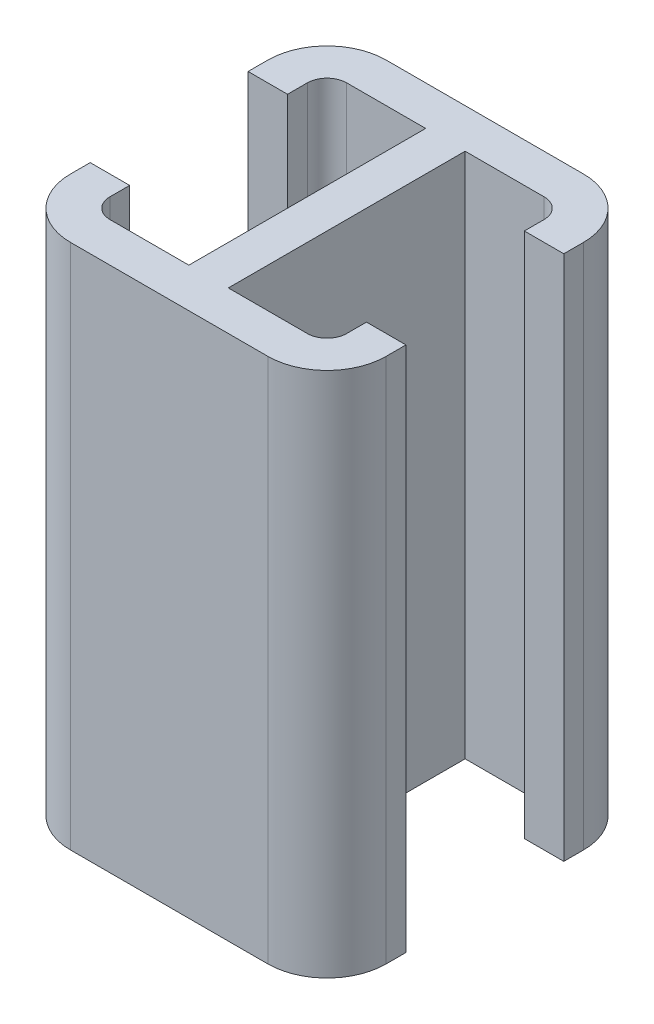
SolidWorks part; units mm, degrees
ref_plane "正面" through (0, 0, 0) normal (0, 0, 1) x (1, 0, 0)
ref_plane "平面" through (0, 0, 0) normal (0, 1, 0) x (1, 0, 0)
ref_plane "右側面" through (0, 0, 0) normal (1, 0, 0) x (0, 0, -1)
sketch "ｽｹｯﾁ5" plane through (0, 0, 0) normal (0, 1, 0) x (1, 0, 0)
  line L1 (0, 0) -> (120, 0)
  line L2 (0, 0) -> (0, 30)
  line L3 (0, 120) -> (120, 120)
  line L4 (120, 0) -> (120, 30)
  line L6 (52.5, 105) -> (15, 105)
  line L7 (52.5, 105) -> (52.5, 15)
  line L8 (52.5, 15) -> (15, 15)
  line L9 (15, 105) -> (15, 90)
  line L11 (15, 90) -> (0, 90)
  line L13 (15, 30) -> (0, 30)
  line L16 (67.5, 105) -> (105, 105)
  line L17 (67.5, 105) -> (67.5, 15)
  line L18 (67.5, 15) -> (105, 15)
  line L19 (105, 105) -> (105, 90)
  line L20 (0, 90) -> (0, 120)
  line L21 (105, 90) -> (120, 90)
  line L23 (105, 30) -> (120, 30)
  line L25 (15, 30) -> (15, 15)
  line L26 (120, 90) -> (120, 120)
  line L27 (105, 30) -> (105, 15)
  point P0 (0, 0)
  point P1 (0, 30)
  point P2 (15.8065, 48.2826)
  point P3 (15, 15)
  point P5 (64.9248, 14.7929)
  point P6 (52.5, 105)
  point P7 (15.8065, 137.9607)
  point P8 (15, 90)
  point P9 (0, 108.5641)
  point P10 (0, 155.4498)
  point P11 (120, 120)
  point P12 (136.7417, 108.5641)
  point P13 (105, 90)
  point P14 (118.8805, 137.9607)
  point P15 (67.5, 105)
  point P16 (84.2744, 14.7929)
  point P17 (105, 15)
  point P18 (118.8805, 48.2826)
  point P19 (120, 30)
  point P20 (136.7417, 0)
  dimension "D1" = 120
  dimension "D2" = 15
  dimension "D3" = 15
  dimension "D4" = 120
  dimension "D5" = 15
  dimension "D6" = 15
  dimension "D7" = 15
  dimension "D8" = 15
  dimension "D9" = 15
  dimension "D10" = 52.5
  dimension "D11" = 30
  dimension "D12" = 30
  dimension "D13" = 30
  dimension "D14" = 30
extrude "ﾎﾞｽ - 押し出し1" add sketch "ｽｹｯﾁ5" along normal blind 200
fillet "ﾌｨﾚｯﾄ1" radius 22.5 4 edges at (0, 100, -120) (0, 100, 0) (120, 100, 0) (120, 100, -120)
fillet "ﾌｨﾚｯﾄ2" radius 7.5 4 edges at (15, 100, -15) (105, 100, -15) (15, 100, -105) (105, 100, -105)
equation "\"C\"= 30"
equation "\"B\"= 15"
equation "\"A\"= 15"
equation "\"D2@ｽｹｯﾁ5\"=\"B\""
equation "\"D3@ｽｹｯﾁ5\"=\"B\""
equation "\"D5@ｽｹｯﾁ5\"=\"B\""
equation "\"D6@ｽｹｯﾁ5\"=\"B\""
equation "\"D7@ｽｹｯﾁ5\"=\"B\""
equation "\"D8@ｽｹｯﾁ5\"=\"B\""
equation "\"D9@ｽｹｯﾁ5\"=\"A\""
equation "\"D11@ｽｹｯﾁ5\"=\"C\""
equation "\"D12@ｽｹｯﾁ5\"=\"C\""
equation "\"D13@ｽｹｯﾁ5\"=\"C\""
equation "\"D14@ｽｹｯﾁ5\"=\"C\""
equation "\"D10@ｽｹｯﾁ5\"=60 - \"A\"/2"
equation "\"D1@ﾌｨﾚｯﾄ1\"=\"B\"/2*3"
equation "\"D1@ﾌｨﾚｯﾄ2\"=\"B\"/2"
